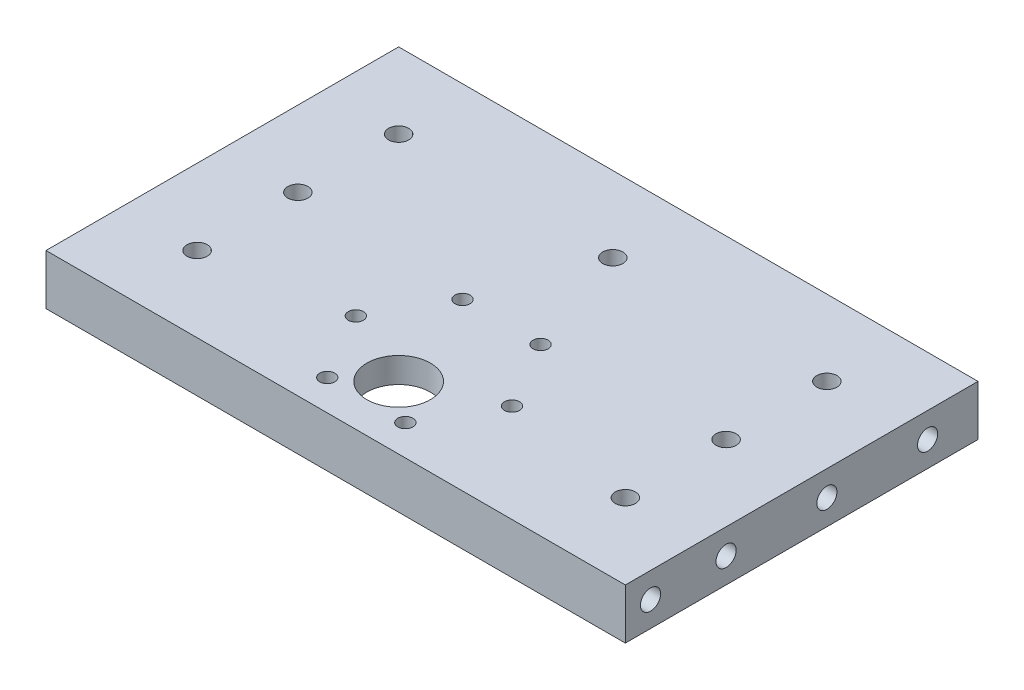
SolidWorks part; units mm, degrees
ref_plane "Front" through (0, 0, 0) normal (0, 0, 1) x (1, 0, 0)
ref_plane "Top" through (0, 0, 0) normal (0, 1, 0) x (1, 0, 0)
ref_plane "Right" through (0, 0, 0) normal (1, 0, 0) x (0, 0, -1)
sketch "Sketch1" plane through (0, 0, 0) normal (0, 1, 0) x (1, 0, 0)
  line L0 (-57.5, 35) -> (57.5, -35) construction
  line L1 (-57.5, 35) -> (57.5, 35)
  line L2 (-57.5, 35) -> (-57.5, -35)
  line L3 (-57.5, -35) -> (57.5, -35)
  line L4 (57.5, 35) -> (57.5, -35)
  dimension "D1" = 115
  dimension "D2" = 70
extrude "Boss-Extrude1" add sketch "Sketch1" along normal blind 10
sketch "Sketch2" plane through (0, 10, 0) normal (0, 1, 0) x (1, 0, 0)
  line L0 (0, -35) -> (0, 35) construction
  line L1 (-57.5, -35) -> (57.5, -35) construction
  line L2 (57.5, 35) -> (-57.5, 35) construction
  line L3 (0, -15.5) -> (15.5, -15.5) construction
  circle A0 centre (0, -15.5) radius 18.5 construction
  circle A1 centre (0, -22.5) radius 6.3
  circle A2 centre (15.5, -15.5) radius 1.5
  circle A3 centre (7.75, -28.9234) radius 1.5
  circle A4 centre (-7.75, -28.9234) radius 1.5
  circle A5 centre (-15.5, -15.5) radius 1.5
  circle A6 centre (-7.75, -2.0766) radius 1.5
  circle A7 centre (7.75, -2.0766) radius 1.5
  point P25 (0, -15.5)
  dimension "D1" = 37
  dimension "D2" = 7
  dimension "D3" = 12.6
  dimension "D4" = 12.5
  dimension "D5" = 3
  dimension "D6" = 15.5
  dimension "D7" = 6
extrude "Cut-Extrude1" cut sketch "Sketch2" against normal blind 10
sketch "Sketch3" plane through (0, 0, 0) normal (0, -1, 0) x (1, 0, 0)
  line L0 (0, 0) -> (0, 35) construction
  line L1 (-57.5, 35) -> (57.5, 35) construction
  circle A0 centre (0, 15.5) radius 18.5
  circle A1 centre (0, 22.5) radius 6.3 construction
  circle A2 centre (0, 22.5) radius 6.3 construction
  point P10 (0, 0)
  dimension "D1" = 37
  dimension "D2" = 7
extrude "Cut-Extrude2" cut sketch "Sketch3" against normal blind 5
sketch "Sketch4" plane through (-57.5, 0, 0) normal (-1, 0, 0) x (0, 0, 1)
  line L0 (30, 5) -> (-35, 5) construction
  line L2 (-35, 10) -> (-35, 0) construction
  line L3 (35, 10) -> (35, 0) construction
  circle A0 centre (30, 5) radius 2
  circle A1 centre (15, 5) radius 2
  circle A2 centre (-5, 5) radius 2
  circle A3 centre (-25, 5) radius 2
  point P0 (28.7444, 5)
  point P14 (0, 0)
  point P15 (0, 0)
  dimension "D1" = 4
  dimension "D2" = 20
  dimension "D3" = 20
  dimension "D4" = 15
  dimension "D5" = 5
extrude "Cut-Extrude3" cut sketch "Sketch4" against normal blind 10
sketch "Sketch5" plane through (57.5, 0, 0) normal (1, 0, 0) x (0, 0, -1)
  circle A0 centre (-30, 5) radius 2 construction
  circle A1 centre (-15, 5) radius 2 construction
  circle A2 centre (5, 5) radius 2 construction
  circle A3 centre (25, 5) radius 2 construction
  circle A4 centre (-30, 5) radius 2
  circle A5 centre (-15, 5) radius 2
  circle A6 centre (5, 5) radius 2
  circle A7 centre (25, 5) radius 2
extrude "Cut-Extrude4" cut sketch "Sketch5" against normal blind 10
sketch "Sketch6" plane through (0, 0, -35) normal (0, 0, -1) x (-1, 0, 0)
  line L0 (-57.5, 5) -> (57.5, 5) construction
  line L1 (-57.5, 10) -> (-57.5, 0) construction
  line L2 (57.5, 10) -> (57.5, 0) construction
  line L3 (0, 0) -> (0, 10) construction
  line L4 (-57.5, 10) -> (57.5, 10) construction
  circle A0 centre (-52.5, 5) radius 2
  circle A3 centre (52.5, 5) radius 2
  point P14 (45.8524, 4.2076)
  dimension "D3" = 4
  dimension "D1" = 5
extrude "Cut-Extrude5" cut sketch "Sketch6" against normal blind 5
sketch "Sketch7" plane through (0, 0, 0) normal (0, -1, 0) x (1, 0, 0)
  line L0 (-42.5, 0) -> (42.5, 0) construction
  line L1 (-42.5, 20) -> (42.5, 20) construction
  line L2 (-42.5, 20) -> (-42.5, -20) construction
  line L3 (-42.5, -20) -> (42.5, -20) construction
  line L4 (42.5, 20) -> (42.5, -20) construction
  line L5 (-57.5, -35) -> (-57.5, 35) construction
  line L6 (0, -35) -> (0, 35) construction
  line L7 (57.5, -35) -> (-57.5, -35) construction
  line L8 (-57.5, 35) -> (57.5, 35) construction
  circle A0 centre (42.5, 20) radius 2
  circle A1 centre (42.5, 0) radius 2
  circle A2 centre (42.5, -20) radius 2
  circle A3 centre (-42.5, -20) radius 2
  circle A4 centre (-42.5, 0) radius 2
  circle A5 centre (-42.5, 20) radius 2
  circle A6 centre (0, -20) radius 2
  dimension "D4" = 4
  dimension "D1" = 15
  dimension "D2" = 15
  dimension "D3" = 15
extrude "Cut-Extrude6" cut sketch "Sketch7" against normal blind 10 contours A3
